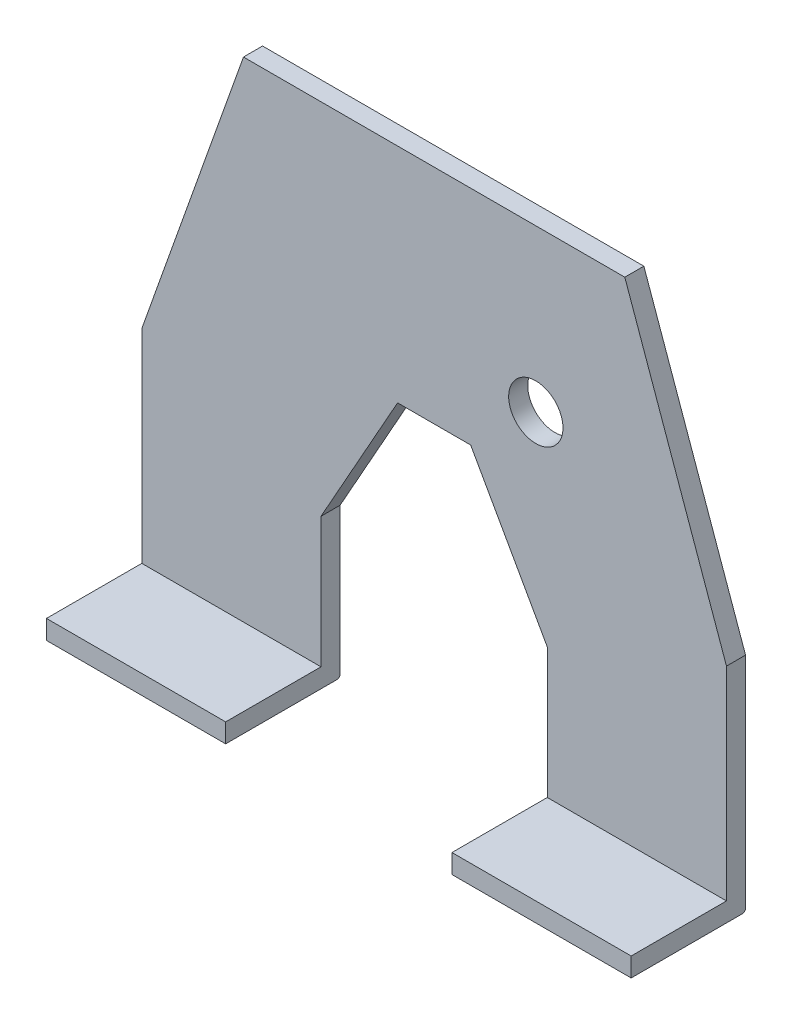
SolidWorks part; units mm, degrees
ref_plane "Alzado" through (0, 0, 0) normal (0, 0, 1) x (1, 0, 0)
ref_plane "Planta" through (0, 0, 0) normal (0, 1, 0) x (1, 0, 0)
ref_plane "Vista lateral" through (0, 0, 0) normal (1, 0, 0) x (0, 0, -1)
sketch "Croquis1" plane through (0, 0, 0) normal (0, 0, 1) x (1, 0, 0)
  line L0 (-46, -40) -> (-46, -5)
  line L1 (46, -40) -> (-46, -40) construction
  line L2 (46, -40) -> (46, 40) construction
  line L3 (46, 40) -> (-46, 40) construction
  line L4 (-46, -40) -> (-46, 40) construction
  line L5 (46, -40) -> (-5.75, 5) construction
  line L6 (46, 40) -> (33.7786, 29.3727) construction
  line L7 (-46, -5) -> (-30, 40)
  line L8 (17.8038, -16.4843) -> (17.8038, -40)
  line L9 (-5.75, 5) -> (5.75, 5)
  line L10 (-17.8038, -16.4843) -> (-17.8038, -40)
  line L11 (-17.8038, -16.4843) -> (-5.75, 5)
  line L12 (0, 0) -> (0, -29.8084) construction
  line L13 (17.8038, -16.4843) -> (5.75, 5)
  line L14 (46, 40) -> (41.4976, 40) construction
  line L15 (46, -40) -> (46, -5)
  line L16 (46, -5) -> (30, 40)
  line L17 (-30, 40) -> (30, 40)
  line L18 (-33.7786, 29.3727) -> (-46, 40) construction
  line L19 (-46, -40) -> (-17.8038, -40)
  line L20 (5.75, 5) -> (-46, -40) construction
  line L21 (17.8038, -40) -> (46, -40)
  circle A0 centre (16, 14.6) radius 4.2718
  point P0 (0, 0)
  point P26 (46, 11.449)
  dimension "D6" = 25.4
  dimension "D1" = 92
  dimension "D2" = 80
  dimension "D3" = 16
  dimension "D4" = 35
  dimension "D5" = 35
  dimension "D7" = 30
extrude "Saliente-Extruir1" add sketch "Croquis1" along normal blind 3
sketch "Croquis2" plane through (0, 0, 0) normal (0, 0, -1) x (-1, 0, 0)
  line L0 (-17.8038, -16.4843) -> (-17.8038, -40) construction
  line L1 (-46, -40) -> (-17.8038, -40)
  line L2 (-46, -40) -> (-46, -37)
  line L3 (-46, -37) -> (-17.8038, -37)
  line L4 (-17.8038, -40) -> (-17.8038, -37)
  line L5 (46, -5) -> (46, -40) construction
  line L6 (17.8038, -40) -> (46, -40)
  line L7 (17.8038, -40) -> (17.8038, -37)
  line L8 (17.8038, -37) -> (46, -37)
  line L9 (46, -40) -> (46, -37)
  dimension "D1" = 3
  dimension "D2" = 3
extrude "Saliente-Extruir2" add sketch "Croquis2" against normal blind 18
fillet "Redondeo2" radius 0.5 2 edges at (-31.9019, -40, 0) (31.9019, -40, 0)
